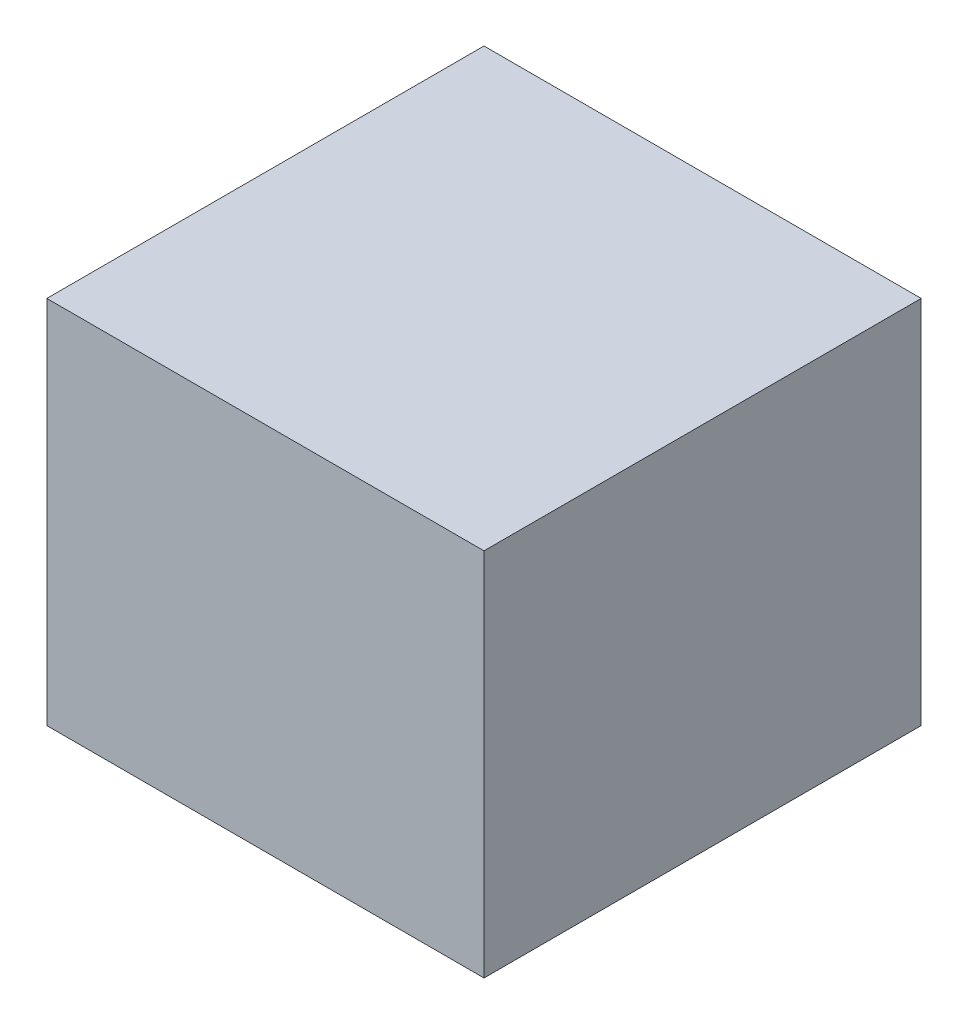
SolidWorks part; units mm, degrees
material "6061-T6 (SS)"
ref_plane "Front Plane" through (0, 0, 0) normal (0, 0, 1) x (1, 0, 0)
ref_plane "Top Plane" through (0, 0, 0) normal (0, 1, 0) x (1, 0, 0)
ref_plane "Right Plane" through (0, 0, 0) normal (1, 0, 0) x (0, 0, -1)
sketch "Sketch1" plane through (0, 0, 0) normal (1, 0, 0) x (0, 0, -1)
  line L1 (-165.1, -139.7) -> (165.1, -139.7)
  line L2 (-165.1, -139.7) -> (-165.1, 139.7)
  line L3 (-165.1, 139.7) -> (165.1, 139.7)
  line L4 (165.1, -139.7) -> (165.1, 139.7)
  line L5 (-165.1, -139.7) -> (165.1, 139.7) construction
  line L6 (-165.1, 139.7) -> (165.1, -139.7) construction
  point P0 (0, 0)
  dimension "D1" = 279.4
  dimension "D2" = 330.2
extrude "Boss-Extrude1" add sketch "Sketch1" along normal mid plane 330.2
